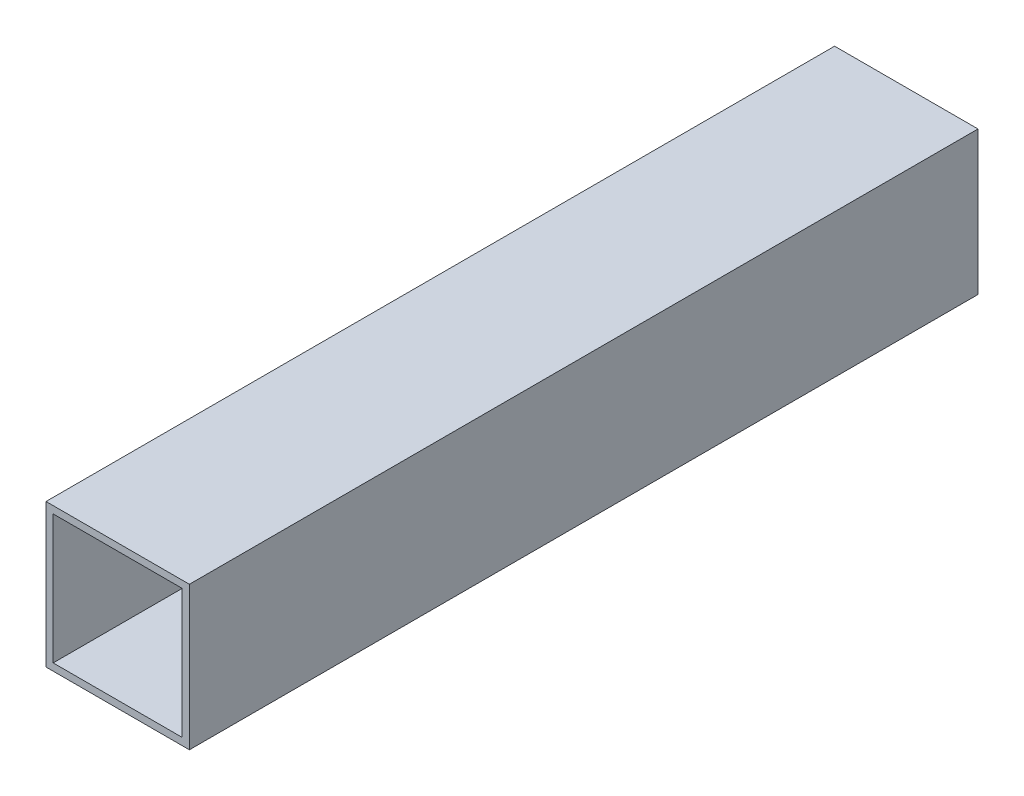
SolidWorks part; units mm, degrees
material "1060-H12"
ref_plane "Alzado" through (0, 0, 0) normal (0, 0, 1) x (1, 0, 0)
ref_plane "Planta" through (0, 0, 0) normal (0, 1, 0) x (1, 0, 0)
ref_plane "Vista lateral" through (0, 0, 0) normal (1, 0, 0) x (0, 0, -1)
sketch "Croquis1" plane through (0, 0, 0) normal (0, 0, 1) x (1, 0, 0)
  line L1 (20, -20) -> (-20, -20)
  line L2 (20, -20) -> (20, 20)
  line L3 (20, 20) -> (-20, 20)
  line L4 (-20, -20) -> (-20, 20)
  line L5 (20, -20) -> (-20, 20) construction
  line L6 (20, 20) -> (-20, -20) construction
  point P0 (0, 0)
  dimension "D1" = 40
  dimension "D2" = 40
extrude "Extruir-Lámina1" add sketch "Croquis1" along normal blind 220 thin
